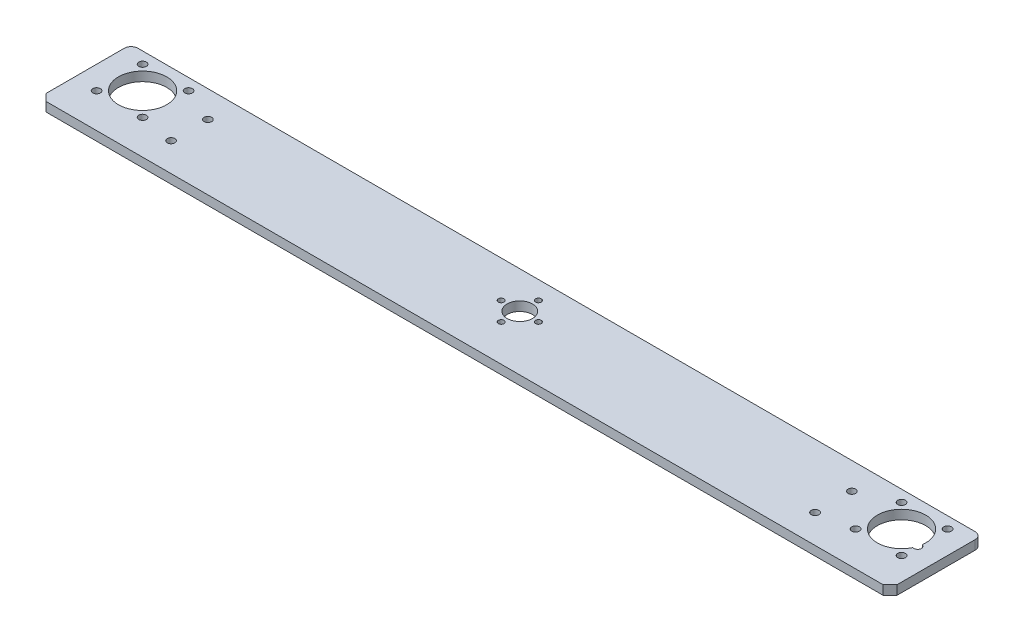
SolidWorks part; units mm, degrees
ref_plane "Front Plane" through (0, 0, 0) normal (0, 0, 1) x (1, 0, 0)
ref_plane "Top Plane" through (0, 0, 0) normal (0, 1, 0) x (1, 0, 0)
ref_plane "Right Plane" through (0, 0, 0) normal (1, 0, 0) x (0, 0, -1)
sketch "Sketch1" plane through (0, 0, 0) normal (0, 1, 0) x (1, 0, 0)
  line L1 (-185, 20) -> (185, 20)
  line L2 (-185, 20) -> (-185, -20)
  line L3 (-185, -20) -> (185, -20)
  line L4 (185, 20) -> (185, -20)
  line L5 (-185, 20) -> (185, -20) construction
  line L6 (-185, -20) -> (185, 20) construction
  point P0 (0, 0)
  dimension "D1" = 40
  dimension "D2" = 370
extrude "Boss-Extrude1" add sketch "Sketch1" along normal blind 4
sketch "Sketch2" plane through (0, 4, 0) normal (0, 1, 0) x (1, 0, 0)
  line L0 (0, 20) -> (0, -20) construction
  line L1 (185, 20) -> (-185, 20) construction
  line L2 (-185, -20) -> (185, -20) construction
  line L3 (-165, 5) -> (165, 5) construction
  circle A0 centre (165, 5) radius 10.5
  circle A1 centre (-165, 5) radius 10.5
  circle A2 centre (0, 4) radius 5.5
  point P15 (0, 5)
  dimension "D1" = 21
  dimension "D4" = 11
  dimension "D2" = 15
  dimension "D3" = 330
  dimension "D5" = 16
extrude "Cut-Extrude1" cut sketch "Sketch2" against normal up to next
hole_wizard "M4x0.7 Tapped Hole1" positions "Sketch6" profile "Sketch7" tap size "M4x0.7" standard "ANSI Metric" end condition up to next
sketch "Sketch6" plane through (0, 4, 0) normal (0, 1, 0) x (1, 0, 0)
  line L6 (115, 2) -> (175, 2) construction
  line L8 (145, 2) -> (145, -13) construction
  line L12 (-140, -7.6107) -> (140, -7.6107) construction
  point P2 (175, 2)
  point P40 (155, 15)
  point P43 (175, 15)
  point P46 (155, -5)
  point P49 (175, -5)
  point P53 (-175, 15)
  point P56 (-155, 15)
  point P59 (-175, -5)
  point P62 (-155, -5)
  point P75 (-140, 8.3942)
  point P77 (-140, -7.6107)
  point P79 (140, 8.3942)
  point P81 (140, -7.6107)
  point P93 (0, -7.6107)
  dimension "D1" = 280
sketch "Sketch7" plane through (175, 4, -2) normal (1, 0, 0) x (0, 0, 1)
  line L0 (0, 0) -> (0, 4)
  line L1 (0, 4) -> (1.65, 4)
  line L2 (1.65, 4) -> (1.65, 0)
  line L5 (1.65, 0) -> (0, 0)
  line L11 (0, -6.35) -> (0, 107.95) construction
  dimension "Thru Tap Drill Dia." = 3.3
  dimension "Thru Tap Drill Depth" = 4
cosmetic thread "Hole Thread1" parameters "D2"=4
cosmetic thread "Hole Thread2" parameters "D2"=4
cosmetic thread "Hole Thread4" parameters "D2"=4
cosmetic thread "Hole Thread5" parameters "D2"=4
cosmetic thread "Hole Thread29" parameters "D2"=4
cosmetic thread "Hole Thread32" parameters "D2"=4
cosmetic thread "Hole Thread33" parameters "D2"=4
cosmetic thread "Hole Thread34" parameters "D2"=4
cosmetic thread "Hole Thread35" parameters "D2"=4
cosmetic thread "Hole Thread36" parameters "D2"=4
cosmetic thread "Hole Thread37" parameters "D2"=4
cosmetic thread "Hole Thread38" parameters "D2"=4
cosmetic thread "Hole Thread39" parameters "D2"=4
chamfer "Chamfer1" distance 3 angle 45 2 edges at (-185, 2, 20) (185, 2, 20)
fillet "Fillet1" radius 3 2 edges at (-185, 2, -20) (185, 2, -20)
hole_wizard "M3x0.5 Tapped Hole1" positions "Sketch8" profile "Sketch9" tap size "M3x0.5" standard "ANSI Metric" end condition up to next
sketch "Sketch8" plane through (0, 4, 0) normal (0, 1, 0) x (1, 0, 0)
  point P0 (0, 12.1)
  point P3 (8.1, 4)
  point P6 (0, -4.1)
  point P9 (-8.1, 4)
sketch "Sketch9" plane through (0, 4, -12.1) normal (1, 0, 0) x (0, 0, 1)
  line L0 (0, 0) -> (0, 4)
  line L1 (0, 4) -> (1.25, 4)
  line L2 (1.25, 4) -> (1.25, 0)
  line L5 (1.25, 0) -> (0, 0)
  line L11 (0, -6.35) -> (0, 107.95) construction
  dimension "Thru Tap Drill Dia." = 2.5
  dimension "Thru Tap Drill Depth" = 4
cosmetic thread "Hole Thread16" parameters "D2"=3
cosmetic thread "Hole Thread18" parameters "D2"=3
cosmetic thread "Hole Thread26" parameters "D2"=3
cosmetic thread "Hole Thread27" parameters "D2"=3
